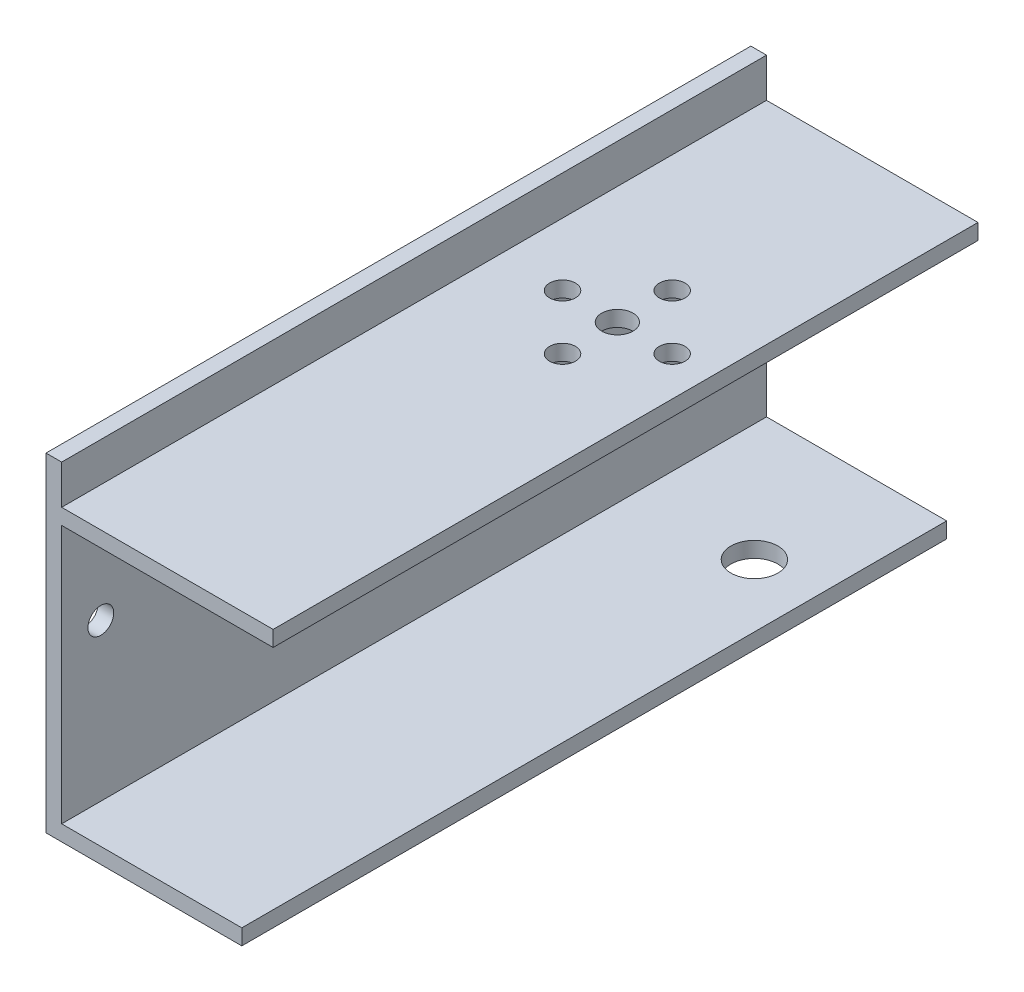
SolidWorks part; units mm, degrees
ref_plane "前视基准面" through (0, 0, 0) normal (0, 0, 1) x (1, 0, 0)
ref_plane "上视基准面" through (0, 0, 0) normal (0, 1, 0) x (1, 0, 0)
ref_plane "右视基准面" through (0, 0, 0) normal (1, 0, 0) x (0, 0, -1)
sketch "草图1" plane through (0, 0, 0) normal (0, 1, 0) x (1, 0, 0)
  line L1 (-12.5, -45) -> (12.5, -45)
  line L2 (-12.5, -45) -> (-12.5, 45)
  line L3 (-12.5, 45) -> (12.5, 45)
  line L4 (12.5, -45) -> (12.5, 45)
  line L5 (-12.5, -45) -> (12.5, 45) construction
  line L6 (-12.5, 45) -> (12.5, -45) construction
  point P1 (0, 0)
  dimension "D1" = 90
  dimension "D2" = 25
extrude "凸台-拉伸1" add sketch "草图1" along normal blind 2
sketch "草图3" plane through (0, 2, 0) normal (0, 1, 0) x (1, 0, 0)
  line L0 (-12.5, -45) -> (12.5, -45) construction
  line L1 (-12.5, 45) -> (-10.5, 45)
  line L2 (-12.5, 45) -> (-12.5, -45)
  line L3 (-12.5, -45) -> (-10.5, -45)
  line L4 (-10.5, 45) -> (-10.5, -45)
  dimension "D1" = 2
extrude "凸台-拉伸2" add sketch "草图3" along normal blind 40
sketch "草图6" plane through (-12.5, 0, 0) normal (-1, 0, 0) x (0, 0, 1)
  line L0 (-45, 21) -> (45, 21) construction
  line L1 (-45, 42) -> (-45, 0) construction
  line L2 (45, 42) -> (45, 0) construction
  circle A0 centre (8, 21) radius 1.65
  circle A1 centre (21.5248, 17.3834) radius 1.65
  circle A2 centre (15, 14) radius 1.65
  circle A3 centre (15, 28) radius 1.65
  dimension "D1" = 3.3
  dimension "D3" = 7
  dimension "D4" = 3.3
  dimension "D7" = 3.3
  dimension "D2" = 30
  dimension "D5" = 14
  dimension "D6" = 37
extrude "切除-拉伸3" cut sketch "草图6" against normal blind 10
sketch "草图7" plane through (0, 0, 0) normal (0, -1, 0) x (-1, 0, 0)
  line L0 (-12.5, 45) -> (12.5, 45) construction
  line L1 (12.5, 45) -> (12.5, -45) construction
  circle A0 centre (-4.5, 28.45) radius 3
  dimension "D3" = 6
  dimension "D1" = 16.55
  dimension "D2" = 17
extrude "切除-拉伸4" cut sketch "草图7" against normal blind 10
sketch "草图8" plane through (-10.5, 0, 0) normal (1, 0, 0) x (0, 0, -1)
  line L0 (-45, 22) -> (45, 22) construction
  line L1 (-45, 42) -> (-45, 2) construction
  line L2 (45, 42) -> (45, 2) construction
  line L3 (0, 42) -> (0, 2) construction
  line L4 (-45, 42) -> (45, 42) construction
  line L5 (-45, 2) -> (45, 2) construction
  circle A0 centre (-40, 22) radius 1.65
  circle A1 centre (40, 22) radius 1.65
  dimension "D1" = 3.3
  dimension "D2" = 3.3
  dimension "D3" = 80
extrude "切除-拉伸5" cut sketch "草图8" against normal blind 10
sketch "草图9" plane through (-10.5, 0, 0) normal (1, 0, 0) x (0, 0, -1)
  line L0 (0, 2) -> (0, 35)
  line L1 (-45, 2) -> (45, 2) construction
  line L2 (0, 35) -> (45, 35)
  line L3 (45, 42) -> (45, 2) construction
  line L4 (45, 35) -> (45, 37)
  line L5 (45, 37) -> (-45, 37)
  line L6 (-45, 42) -> (-45, 2) construction
  line L7 (-45, 37) -> (-45, 35)
  line L8 (-45, 35) -> (0, 35)
  line M8 (45, 2) -> (45, 42)
  line M10 (-45, 42) -> (-45, 2)
extrude "凸台-拉伸3" add sketch "草图9" along normal blind 27 contours L8 L2 L5 M10 M8
sketch "草图10" plane through (0, 35, 0) normal (0, -1, 0) x (1, 0, 0)
  line L0 (4.5, -28.45) -> (4.5, -23.45)
  line L1 (4.5, -28.45) -> (4.5, -10.95)
  line L2 (4.5, -10.95) -> (11.5, -10.95)
  circle A4 centre (4.5, -10.95) radius 2
  circle A5 centre (11.5, -10.95) radius 1.65
  circle A6 centre (4.5, -17.95) radius 1.65
  circle A7 centre (-2.5, -10.95) radius 1.65
  circle A8 centre (4.5, -3.95) radius 1.65
  point P13 (4.5, -28.45)
  point P18 (4.5, -10.95)
  dimension "D1" = 4
extrude "切除-拉伸7" cut sketch "草图10" against normal blind 6
